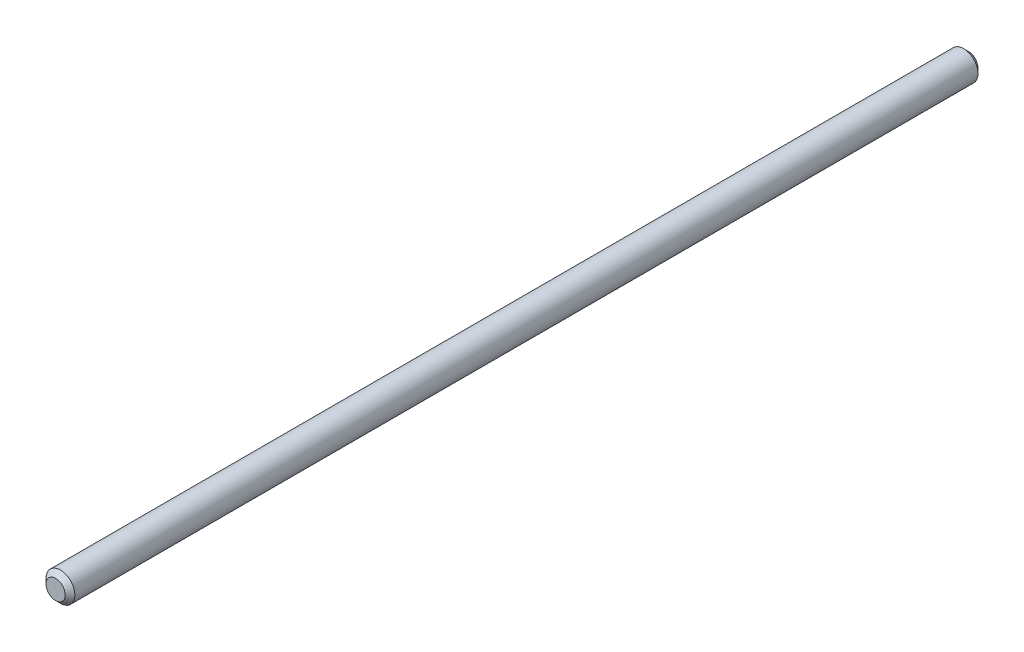
SolidWorks part; units mm, degrees
ref_plane "Front Plane" through (0, 0, 0) normal (0, 0, 1) x (1, 0, 0)
ref_plane "Top Plane" through (0, 0, 0) normal (0, 1, 0) x (1, 0, 0)
ref_plane "Right Plane" through (0, 0, 0) normal (1, 0, 0) x (0, 0, -1)
sketch "Sketch1" plane through (0, 0, 0) normal (0, 0, 1) x (1, 0, 0)
  circle A0 centre (0, 0) radius 3
  dimension "D1" = 6
extrude "Boss-Extrude1" add sketch "Sketch1" along normal mid plane 189.7
chamfer "Chamfer1" distance 1 angle 45 2 edges at (3, 0, -94.85) (3, 0, 94.85)
